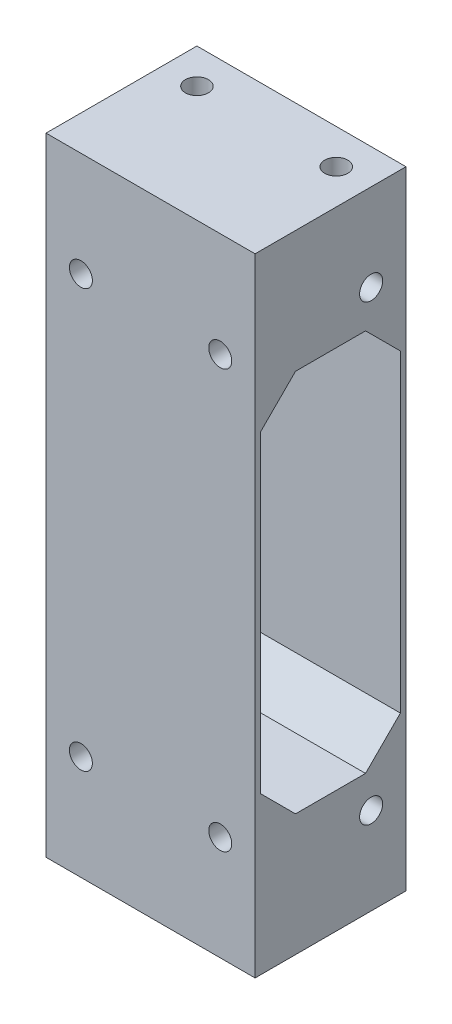
SolidWorks part; units mm, degrees
ref_plane "Front Plane" through (0, 0, 0) normal (0, 0, 1) x (1, 0, 0)
ref_plane "Top Plane" through (0, 0, 0) normal (0, 1, 0) x (1, 0, 0)
ref_plane "Right Plane" through (0, 0, 0) normal (1, 0, 0) x (0, 0, -1)
sketch "Sketch1" plane through (0, 0, 0) normal (0, 1, 0) x (1, 0, 0)
  line L1 (-15, -10.825) -> (15, -10.825)
  line L2 (-15, -10.825) -> (-15, 10.825)
  line L3 (-15, 10.825) -> (15, 10.825)
  line L4 (15, -10.825) -> (15, 10.825)
  line L5 (-15, -10.825) -> (15, 10.825) construction
  line L6 (-15, 10.825) -> (15, -10.825) construction
  point P0 (0, 0)
  dimension "D1" = 21.65
  dimension "D2" = 30
extrude "Boss-Extrude1" add sketch "Sketch1" along normal blind 90
hole_wizard "M4x0.7 Tapped Hole1" positions "Sketch2" profile "Sketch4" tap size "M4x0.7" standard "ANSI Metric"
sketch "Sketch2" plane through (0, 90, 0) normal (0, 1, 0) x (1, 0, 0)
  line L0 (-10, 5.825) -> (10, 5.825)
  line L4 (15, 10.825) -> (-15, 10.825) construction
  point P1 (-10, 5.825)
  point P2 (10, 5.825)
  point P7 (0, 5.825)
  dimension "D1" = 5
  dimension "D2" = 20
sketch "Sketch4" plane through (-10, 90, -5.825) normal (1, 0, 0) x (0, 0, 1)
  line L0 (0, 0) -> (0, 10.9914)
  line L1 (0, 10.9914) -> (1.65, 10)
  line L2 (1.65, 10) -> (1.65, 0)
  line L5 (1.65, 0) -> (0, 0)
  line L10 (0, 10.9914) -> (-1.65, 10) construction
  line L11 (0, -6.35) -> (0, 107.95) construction
  dimension "Tap Drill Dia." = 3.3
  dimension "Tap Drill Depth" = 10
  dimension "Drill Angle" = 118
cosmetic thread "Hole Thread1" parameters "D1"=8, "D2"=4
cosmetic thread "Hole Thread2" parameters "D1"=8, "D2"=4
hole_wizard "M4x0.7 Tapped Hole2" positions "Sketch5" profile "Sketch6" tap size "M4x0.7" standard "ANSI Metric"
sketch "Sketch5" plane through (0, 0, 0) normal (0, -1, 0) x (-1, 0, 0)
  line L0 (-10, -0.825) -> (10, -0.825)
  line L2 (15, -10.825) -> (-15, -10.825) construction
  point P1 (-10, -0.825)
  point P2 (10, -0.825)
  point P4 (0, -0.825)
  dimension "D1" = 10
  dimension "D2" = 20
sketch "Sketch6" plane through (10, 0, 0.825) normal (1, 0, 0) x (0, 0, -1)
  line L0 (0, 0) -> (0, 12.9914)
  line L1 (0, 12.9914) -> (1.65, 12)
  line L2 (1.65, 12) -> (1.65, 0)
  line L5 (1.65, 0) -> (0, 0)
  line L10 (0, 12.9914) -> (-1.65, 12) construction
  line L11 (0, -6.35) -> (0, 107.95) construction
  dimension "Tap Drill Dia." = 3.3
  dimension "Tap Drill Depth" = 12
  dimension "Drill Angle" = 118
cosmetic thread "Hole Thread3" parameters "D1"=8, "D2"=4
cosmetic thread "Hole Thread4" parameters "D1"=8, "D2"=4
sketch "Sketch7" plane through (15, 0, 0) normal (1, 0, 0) x (0, 0, -1)
  line L1 (-10.025, 17.5) -> (10.025, 17.5)
  line L2 (-10.025, 17.5) -> (-10.025, 72.5)
  line L3 (-10.025, 72.5) -> (10.025, 72.5)
  line L4 (10.025, 17.5) -> (10.025, 72.5)
  line L5 (-10.025, 17.5) -> (10.025, 72.5) construction
  line L6 (-10.025, 72.5) -> (10.025, 17.5) construction
  line L7 (-10.825, 90) -> (10.825, 90) construction
  line L8 (10.825, 90) -> (10.825, 0) construction
  point P0 (0, 45)
  point P7 (0, 0)
  dimension "D1" = 20.05
  dimension "D2" = 45
  dimension "D3" = 17.5
  dimension "D4" = 20.05
  dimension "D5" = 0.8
extrude "Cut-Extrude1" cut sketch "Sketch7" against normal through all
chamfer "Chamfer1" distance 5 angle 45 4 edges at (0, 72.5, 10.025) (0, 72.5, -10.025) (0, 17.5, -10.025) (0, 17.5, 10.025)
hole_wizard "M4x0.7 Tapped Hole3" positions "Sketch8" profile "Sketch9" tap size "M4x0.7" standard "ANSI Metric"
sketch "Sketch8" plane through (0, 0, 10.825) normal (0, 0, 1) x (1, 0, 0)
  line L0 (-15, 0) -> (15, 0) construction
  line L1 (-15, 90) -> (-15, 0) construction
  point P0 (-10, 15)
  point P11 (10, 15)
  point P12 (10, 75)
  point P13 (-10, 75)
  dimension "D1" = 15
  dimension "D2" = 5
  dimension "D3" = 2
  dimension "D4" = 2
sketch "Sketch9" plane through (-10, 15, 10.825) normal (1, 0, 0) x (0, -1, 0)
  line L0 (0, 0) -> (0, 10.9914)
  line L1 (0, 10.9914) -> (1.65, 10)
  line L2 (1.65, 10) -> (1.65, 0)
  line L5 (1.65, 0) -> (0, 0)
  line L10 (0, 10.9914) -> (-1.65, 10) construction
  line L11 (0, -6.35) -> (0, 107.95) construction
  dimension "Tap Drill Dia." = 3.3
  dimension "Tap Drill Depth" = 10
  dimension "Drill Angle" = 118
cosmetic thread "Hole Thread5" parameters "D1"=8, "D2"=4
cosmetic thread "Hole Thread6" parameters "D1"=8, "D2"=4
cosmetic thread "Hole Thread7" parameters "D1"=8, "D2"=4
cosmetic thread "Hole Thread8" parameters "D1"=8, "D2"=4
hole_wizard "M4x0.7 Tapped Hole4" positions "Sketch11" profile "Sketch12" tap size "M4x0.7" standard "ANSI Metric"
sketch "Sketch11" plane through (15, 0, 0) normal (1, 0, 0) x (0, 0, -1)
  line L0 (5.825, 12.5) -> (5.825, 77.5)
  line L1 (10.825, 90) -> (10.825, 0) construction
  line L2 (-10.825, 0) -> (10.825, 0) construction
  point P0 (5.825, 12.5)
  point P1 (5.825, 77.5)
  dimension "D1" = 5
  dimension "D2" = 65
  dimension "D3" = 12.5
sketch "Sketch12" plane through (15, 12.5, -5.825) normal (0, 1, 0) x (0, 0, -1)
  line L0 (0, 0) -> (0, 8.9914)
  line L1 (0, 8.9914) -> (1.65, 8)
  line L2 (1.65, 8) -> (1.65, 0)
  line L5 (1.65, 0) -> (0, 0)
  line L10 (0, 8.9914) -> (-1.65, 8) construction
  line L11 (0, -6.35) -> (0, 107.95) construction
  dimension "Tap Drill Dia." = 3.3
  dimension "Tap Drill Depth" = 8
  dimension "Drill Angle" = 118
cosmetic thread "Hole Thread9" parameters "D1"=8, "D2"=4
cosmetic thread "Hole Thread10" parameters "D1"=8, "D2"=4
